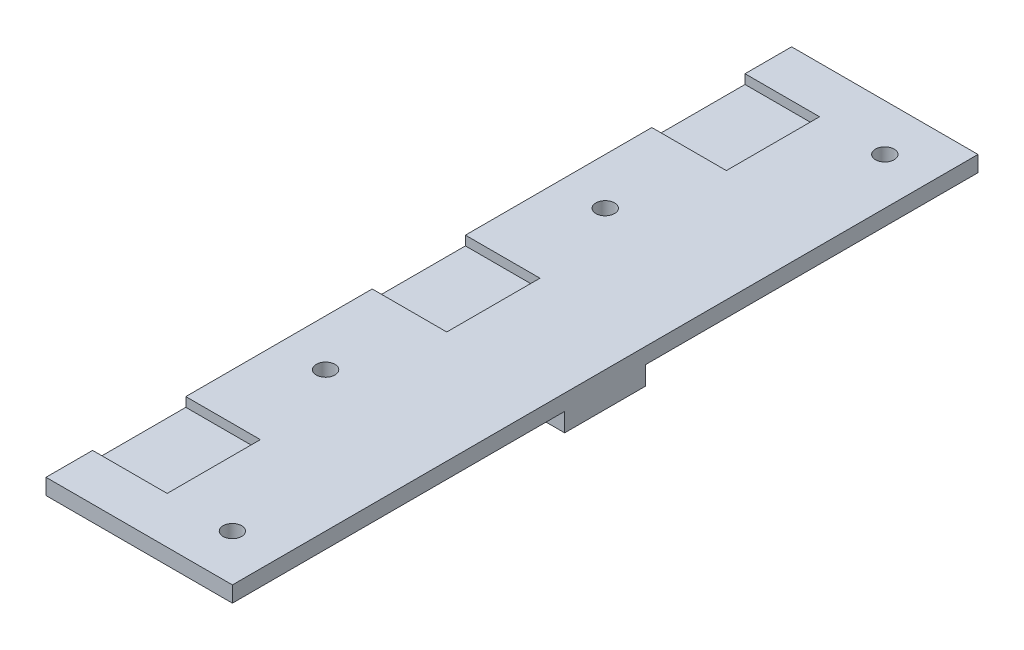
SolidWorks part; units mm, degrees
ref_plane "前视基准面" through (0, 0, 0) normal (0, 0, 1) x (1, 0, 0)
ref_plane "上视基准面" through (0, 0, 0) normal (0, 1, 0) x (1, 0, 0)
ref_plane "右视基准面" through (0, 0, 0) normal (1, 0, 0) x (0, 0, -1)
other "Configuration Table"
sketch "草图1" plane through (0, 0, 0) normal (0, 1, 0) x (1, 0, 0)
  line L22 (-10, -40) -> (10, -40)
  line L23 (-10, -40) -> (-10, 40)
  line L28 (-10, 40) -> (10, 40)
  line L29 (10, -40) -> (10, 40)
  line L37 (-10, -40) -> (10, 40) construction
  line L38 (-10, 40) -> (10, -40) construction
  circle A1 centre (-5, 15) radius 1
  circle A2 centre (-5, -15) radius 1
  circle A3 centre (5, 35) radius 1
  circle A4 centre (5, -35) radius 1
  point P0 (0, 0)
  dimension "D3" = 2
  dimension "D9" = 25
  dimension "D1" = 20
  dimension "D2" = 80
  dimension "D4" = 5
  dimension "D5" = 5
  dimension "D6" = 5
  dimension "D7" = 5
  dimension "D8" = 5
  dimension "D10" = 5
  dimension "D11" = 25
extrude "凸台-拉伸1" add sketch "草图1" along normal blind 1.7
sketch "草图2" plane through (0, 1.7, 0) normal (0, 1, 0) x (1, 0, 0)
  line L0 (-10, 40) -> (-10, -40) construction
  line L1 (-10, -25) -> (-2, -25)
  line L2 (-10, -25) -> (-10, -35)
  line L3 (-10, -35) -> (-2, -35)
  line L4 (-2, -25) -> (-2, -35)
  line L5 (-2, 0) -> (-10, 0) construction
  line L6 (-10, 5) -> (-2, 5)
  line L7 (-10, 5) -> (-10, -5)
  line L8 (-10, -5) -> (-2, -5)
  line L9 (-2, 5) -> (-2, -5)
  line L10 (-10, 35) -> (-2, 35)
  line L11 (-10, 35) -> (-10, 25)
  line L12 (-10, 25) -> (-2, 25)
  line L13 (-2, 35) -> (-2, 25)
  line L14 (-2, 30) -> (-10, 30) construction
  line L15 (-2, -30) -> (-10, -30) construction
  line L16 (-10, -40) -> (10, -40) construction
  dimension "D1" = 10
  dimension "D2" = 40
  dimension "D3" = 70
  dimension "D4" = 10
  dimension "D5" = 8
extrude "切除-拉伸1" cut sketch "草图2" against normal blind 1
sketch "草图3" plane through (0, 0, 0) normal (0, -1, 0) x (1, 0, 0)
  line L0 (10, 40) -> (10, -40) construction
  line L1 (10, -4.35) -> (4.6, -4.35)
  line L2 (10, -4.35) -> (10, 4.35)
  line L3 (10, 4.35) -> (4.6, 4.35)
  line L4 (4.6, -4.35) -> (4.6, 4.35)
  line L5 (4.6, 0) -> (0, 0) construction
  dimension "D1" = 8.7
  dimension "D2" = 5.4
extrude "凸台-拉伸2" add sketch "草图3" along normal blind 2
